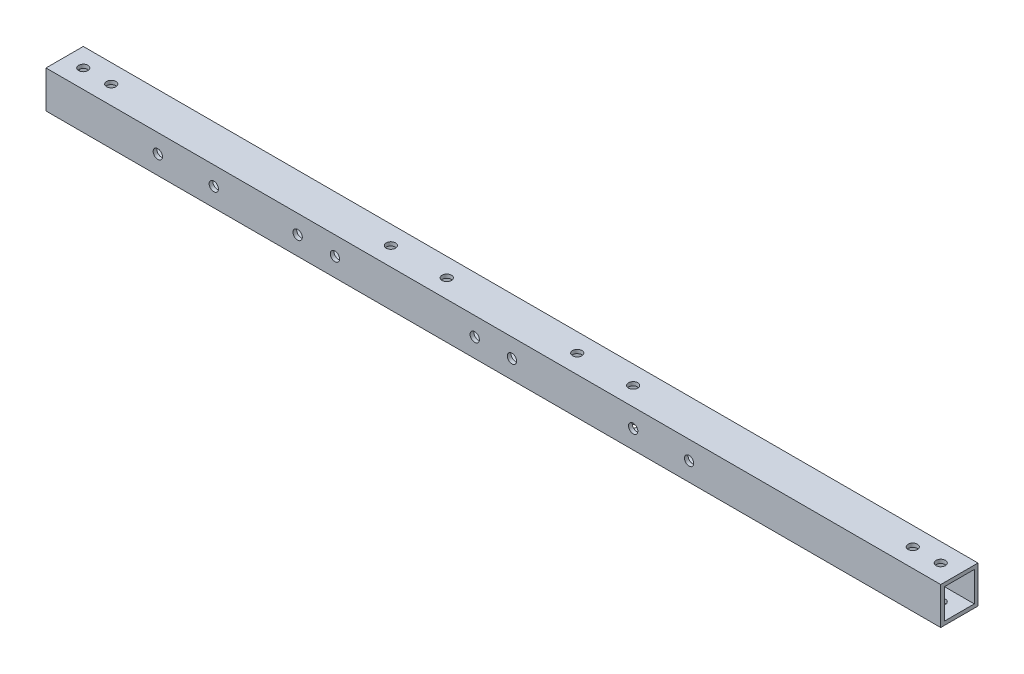
SolidWorks part; units mm, degrees
material "1345 Alloy"
ref_plane "Front Plane" through (0, 0, 0) normal (0, 0, 1) x (1, 0, 0)
ref_plane "Top Plane" through (0, 0, 0) normal (0, 1, 0) x (1, 0, 0)
ref_plane "Right Plane" through (0, 0, 0) normal (1, 0, 0) x (0, 0, -1)
sketch "Sketch1" plane through (0, 0, 0) normal (1, 0, 0) x (0, 0, -1)
  line L1 (-10, 10) -> (10, 10)
  line L2 (-10, 10) -> (-10, -10)
  line L3 (-10, -10) -> (10, -10)
  line L4 (10, 10) -> (10, -10)
  line L5 (-10, 10) -> (10, -10) construction
  line L6 (-10, -10) -> (10, 10) construction
  line L7 (-8, 8) -> (8, 8)
  line L8 (-8, 8) -> (-8, -8)
  line L9 (-8, -8) -> (8, -8)
  line L10 (8, 8) -> (8, -8)
  line L11 (-8, 8) -> (8, -8) construction
  line L12 (-8, -8) -> (8, 8) construction
  point P0 (0, 0)
  point P6 (0, 0)
  dimension "D1" = 20
  dimension "D2" = 20
  dimension "D3" = 16
  dimension "D4" = 16
extrude "Boss-Extrude1" add sketch "Sketch1" along normal blind 480
sketch "Sketch2" plane through (0, 10, 0) normal (0, 1, 0) x (1, 0, 0)
  line L0 (-16.9319, 0) -> (495.2657, 0) construction
  line L1 (480, 10) -> (480, -10) construction
  line L2 (0, 10) -> (0, -10) construction
  line L3 (10, 31.8777) -> (10, -17.8515) construction
  line L4 (470, 25.7534) -> (470, -31.8149) construction
  circle A0 centre (10, 0) radius 2.5
  circle A1 centre (470, 0) radius 2.5
  circle A3 centre (25, 0) radius 2.5
  circle A4 centre (455, 0) radius 2.5
  dimension "D1" = 5
  dimension "D2" = 5
  dimension "D7" = 15
  dimension "D3" = 10
  dimension "D4" = 10
  dimension "D8" = 15
  dimension "D5" = 2
  dimension "D6" = 2
extrude "Cut-Extrude1" cut sketch "Sketch2" against normal through all
sketch "Sketch3" plane through (0, 10, 0) normal (0, 1, 0) x (1, 0, 0)
  line L0 (240, 10) -> (240, -82.7489) construction
  line L1 (480, 10) -> (0, 10) construction
  line L2 (-51.465, 0) -> (614.1502, 0) construction
  line L3 (0, 10) -> (0, -10) construction
  line L4 (190, 28.9336) -> (190, -25.8549) construction
  circle A0 centre (175, 0) radius 2.5
  circle A1 centre (305, 0) radius 2.5
  circle A2 centre (205, 0) radius 2.5
  circle A3 centre (275, 0) radius 2.5
  dimension "D1" = 5
  dimension "D2" = 175
  dimension "D3" = 15
extrude "Cut-Extrude2" cut sketch "Sketch3" against normal through all
sketch "Sketch4" plane through (0, 0, 10) normal (0, 0, 1) x (1, 0, 0)
  line L0 (0, 0) -> (147.7001, 0) construction
  line L1 (480, 10) -> (0, 10) construction
  circle A0 centre (60, 0) radius 2.5
  circle A1 centre (90, 0) radius 2.5
  circle A2 centre (315, 0) radius 2.5
  circle A3 centre (345, 0) radius 2.5
  circle A4 centre (135, 0) radius 2.5
  circle A5 centre (155, 0) radius 2.5
  circle A6 centre (230, 0) radius 2.5
  circle A7 centre (250, 0) radius 2.5
  dimension "D1" = 5
  dimension "D4" = 5
  dimension "D7" = 5
  dimension "D8" = 5
  dimension "D10" = 20
  dimension "D11" = 75
  dimension "D12" = 20
  dimension "D13" = 5
  dimension "D14" = 5
  dimension "D15" = 5
  dimension "D16" = 5
  dimension "D2" = 30
  dimension "D3" = 60
  dimension "D5" = 30
  dimension "D6" = 10
  dimension "D9" = 45
extrude "Cut-Extrude3" cut sketch "Sketch4" against normal blind 20
